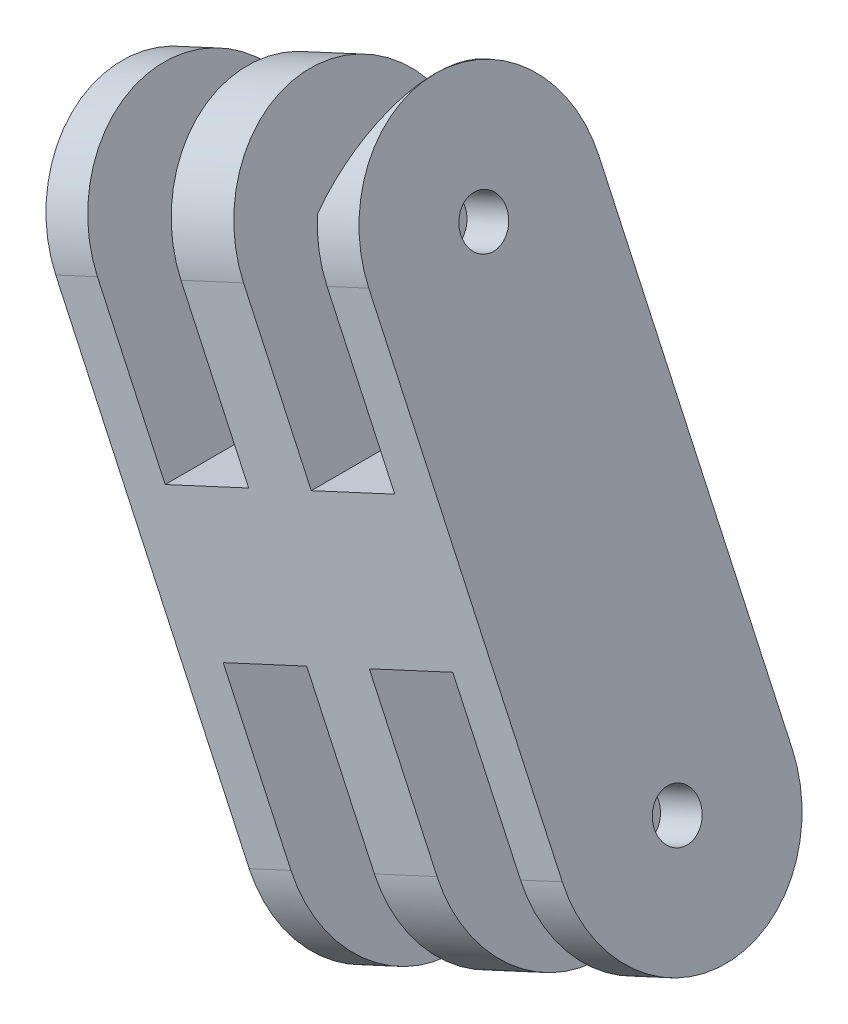
SolidWorks part; units mm, degrees
ref_plane "Plan de face" through (0, 0, 0) normal (0, 0, 1) x (1, 0, 0)
ref_plane "Plan de dessus" through (0, 0, 0) normal (0, 1, 0) x (1, 0, 0)
ref_plane "Plan de droite" through (0, 0, 0) normal (1, 0, 0) x (0, 0, -1)
sketch "Esquisse1" plane through (0, 0, 0) normal (0, 0, 1) x (1, 0, 0)
  line L0 (-112.5526, 133.963) -> (-99.9356, 106.7451)
  line L1 (-112.5526, 133.963) -> (-98.9437, 140.2715)
  line L2 (-99.9356, 106.7451) -> (-86.3267, 113.0536)
  line L3 (-98.9437, 140.2715) -> (-86.3267, 113.0536)
  line L4 (-112.5526, 133.963) -> (-86.3267, 113.0536) construction
  line L5 (-99.9356, 106.7451) -> (-98.9437, 140.2715) construction
  line L6 (-98.1211, 107.5863) -> (-103.1679, 118.4734)
  line L7 (-95.234, 114.4357) -> (-103.6453, 132.5809) construction
  line L8 (-112.5526, 133.963) -> (-110.7381, 134.8041)
  line L9 (-110.7381, 134.8041) -> (-105.6913, 123.917)
  line L10 (-105.6913, 123.917) -> (-95.7114, 128.5432)
  line L11 (-95.7114, 128.5432) -> (-99.587, 136.9037)
  line L13 (-99.587, 136.9037) -> (-98.9437, 140.2715)
  line L14 (-103.1679, 118.4734) -> (-93.188, 123.0996)
  line L15 (-93.188, 123.0996) -> (-88.1412, 112.2125)
  line L16 (-99.5389, 120.1557) -> (-94.4921, 109.2685)
  line L17 (-94.4921, 109.2685) -> (-91.7703, 110.5302)
  line L18 (-91.7703, 110.5302) -> (-96.8171, 121.4174)
  line L19 (-102.0623, 125.5992) -> (-107.1091, 136.4864)
  line L20 (-107.1091, 136.4864) -> (-104.3873, 137.7481)
  line L21 (-104.3873, 137.7481) -> (-99.3405, 126.8609)
  line L22 (-107.1091, 136.4864) -> (-104.3873, 137.7481)
  line L23 (-102.0623, 125.5992) -> (-99.3405, 126.8609)
  line L24 (-94.4921, 109.2685) -> (-91.7703, 110.5302)
  line L25 (-99.5389, 120.1557) -> (-96.8171, 121.4174)
  line L26 (-99.5389, 120.1557) -> (-94.4921, 109.2685)
  line L27 (-99.5389, 120.1557) -> (-96.8171, 121.4174)
  line L28 (-94.4921, 109.2685) -> (-91.7703, 110.5302)
  line L29 (-96.8171, 121.4174) -> (-91.7703, 110.5302)
  line L30 (-107.1091, 136.4864) -> (-102.0623, 125.5992)
  line L31 (-107.1091, 136.4864) -> (-104.3873, 137.7481)
  line L32 (-102.0623, 125.5992) -> (-99.3405, 126.8609)
  line L33 (-104.3873, 137.7481) -> (-99.3405, 126.8609)
  point P1 (-99.4397, 123.5083)
  point P8 (-99.4397, 123.5083)
  dimension "D1" = 30
  dimension "D2" = 15
  dimension "D3" = 12
  dimension "D4" = 2
  dimension "D5" = 2
  dimension "D6" = 2
  dimension "D7" = 2
  dimension "D8" = 3
  dimension "D9" = 3
  dimension "D10" = 4
  dimension "D11" = 12
  dimension "D12" = 4
extrude "Boss.-Extru.1" add sketch "Esquisse1" along normal blind 10 contours L11 L10 L9 L1 L0 L2 L3 | L30 L31 L33 L32 | L26 L27 L29 L28
sketch "Esquisse2" plane through (-27.9204, -12.9427, 0) normal (0.9073, 0.4206, 0) x (0, 0, -1)
  line L0 (-10, 163.8754) -> (0, 163.8754) construction
  line L1 (-10, 168.8754) -> (-10, 138.8754) construction
  line L2 (0, 168.8754) -> (0, 138.8754) construction
  line L3 (-10, 143.8754) -> (0, 143.8754) construction
  line L4 (-10, 168.8754) -> (0, 168.8754) construction
  line L5 (-10, 138.8754) -> (0, 138.8754) construction
  arc A0 (-10, 163.8754) -> (0, 163.8754) centre (-5, 163.8754) cw
  arc A1 (0, 143.8754) -> (-10, 143.8754) centre (-5, 143.8754) cw
  circle A2 centre (-5, 163.8754) radius 1
  circle A3 centre (-5, 143.8754) radius 1
  dimension "D3" = 2
  dimension "D4" = 2
  dimension "D1" = 5
  dimension "D2" = 5
extrude "Enlèv. mat.-Extru.1" cut sketch "Esquisse2" against normal blind 15
